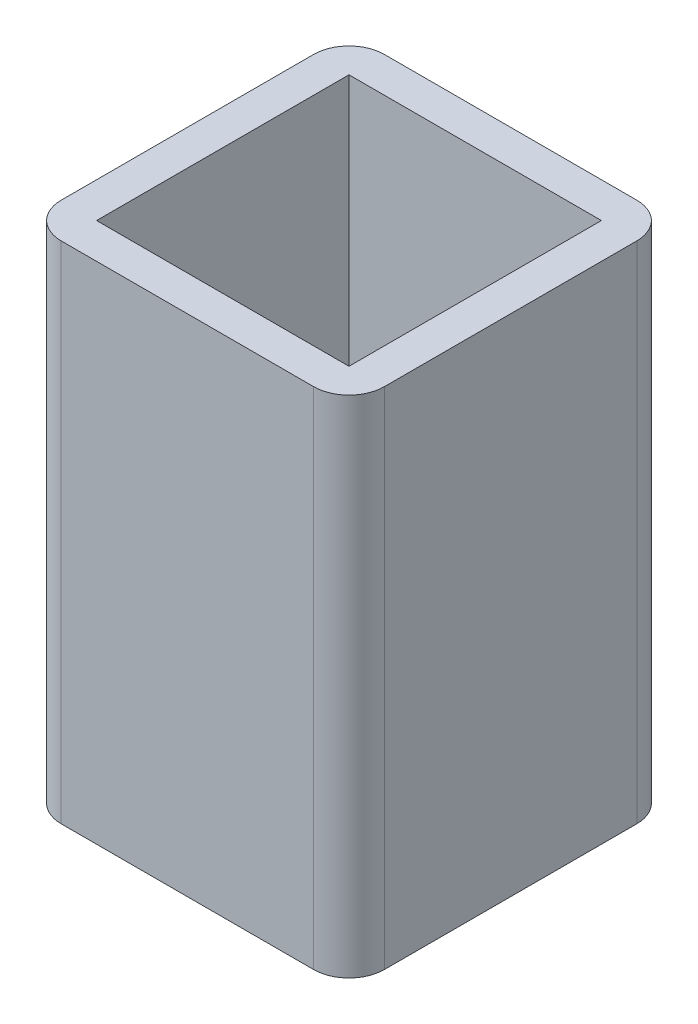
SolidWorks part; units mm, degrees
ref_plane "Front Plane" through (0, 0, 0) normal (0, 0, 1) x (1, 0, 0)
ref_plane "Top Plane" through (0, 0, 0) normal (0, 1, 0) x (1, 0, 0)
ref_plane "Right Plane" through (0, 0, 0) normal (1, 0, 0) x (0, 0, -1)
sketch "Sketch1" plane through (0, 0, 0) normal (0, 1, 0) x (1, 0, 0)
  line L1 (2.8, 0) -> (22.8, 0)
  line L2 (0, -2.8) -> (0, -22.8)
  line L3 (2.8, -25.6) -> (22.8, -25.6)
  line L4 (25.6, -2.8) -> (25.6, -22.8)
  arc A0 (22.8, 0) -> (25.6, -2.8) centre (22.8, -2.8) cw
  arc A1 (22.8, -25.6) -> (25.6, -22.8) centre (22.8, -22.8) ccw
  arc A2 (0, -22.8) -> (2.8, -25.6) centre (2.8, -22.8) ccw
  arc A3 (2.8, 0) -> (0, -2.8) centre (2.8, -2.8) ccw
  point P7 (25.6, 0)
  point P10 (25.6, -25.6)
  point P15 (0, 0)
  dimension "D2" = 2.8
  dimension "D1" = 25.6
extrude "Boss-Extrude1" add sketch "Sketch1" along normal blind 40
sketch "Sketch3" plane through (0, 0, 0) normal (0, -1, 0) x (-1, 0, 0)
  line L4 (-2.8, -2.8) -> (-22.8, -2.8)
  line L5 (-2.8, -2.8) -> (-2.8, -22.8)
  line L6 (-2.8, -22.8) -> (-22.8, -22.8)
  line L7 (-22.8, -2.8) -> (-22.8, -22.8)
  line L8 (-2.8, -2.8) -> (-22.8, -22.8) construction
  line L9 (-2.8, -22.8) -> (-22.8, -2.8) construction
  point P6 (-12.8, -12.8)
extrude "Cut-Extrude1" cut sketch "Sketch3" against normal blind 1040.5
